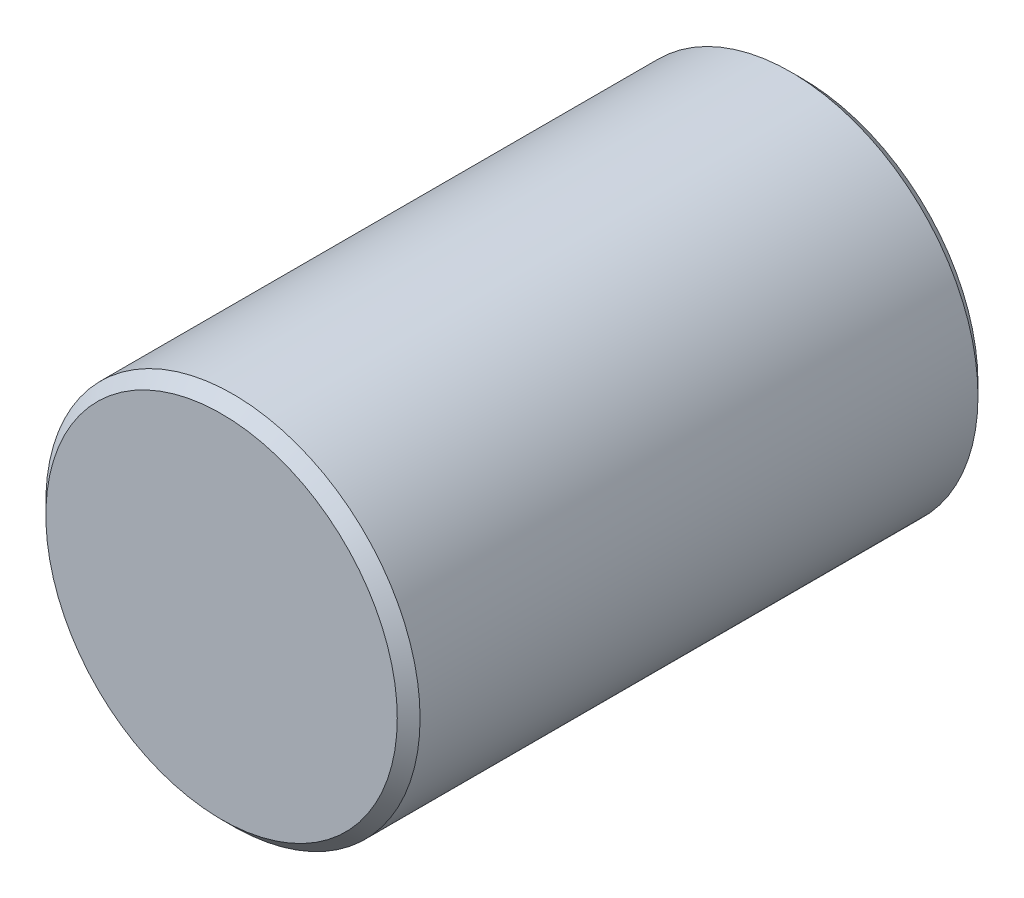
SolidWorks part; units mm, degrees
ref_plane "Front Plane" through (0, 0, 0) normal (0, 0, 1) x (1, 0, 0)
ref_plane "Top Plane" through (0, 0, 0) normal (0, 1, 0) x (1, 0, 0)
ref_plane "Right Plane" through (0, 0, 0) normal (1, 0, 0) x (0, 0, -1)
sketch "Sketch1" plane through (0, 0, 0) normal (0, 0, 1) x (1, 0, 0)
  circle A0 centre (0, 0) radius 5.8
extrude "Boss-Extrude1" add sketch "Sketch1" along normal mid plane 18
sketch "Sketch2" plane through (0, 0, 0) normal (1, 0, 0) x (0, 0, -1)
  line L0 (8.6465, 5.8) -> (9, 5.4465)
  line L1 (9, 5.8) -> (-9, 5.8) construction
  line L2 (9, -5.8) -> (9, 5.8) construction
  line L3 (-9, 5.4465) -> (-8.6465, 5.8)
  line L4 (-9, 5.8) -> (-9, -5.8) construction
  line L5 (-8.6465, 5.8) -> (-9, 5.8)
  line L6 (-9, 5.8) -> (-9, 5.4465)
  line L7 (9, 5.4465) -> (9, 5.8)
  line L8 (9, 5.8) -> (8.6465, 5.8)
  line L9 (-11.1013, 0) -> (10.7631, 0) construction
revolve "Cut-Revolve1" cut sketch "Sketch2" angle 360 about L9
